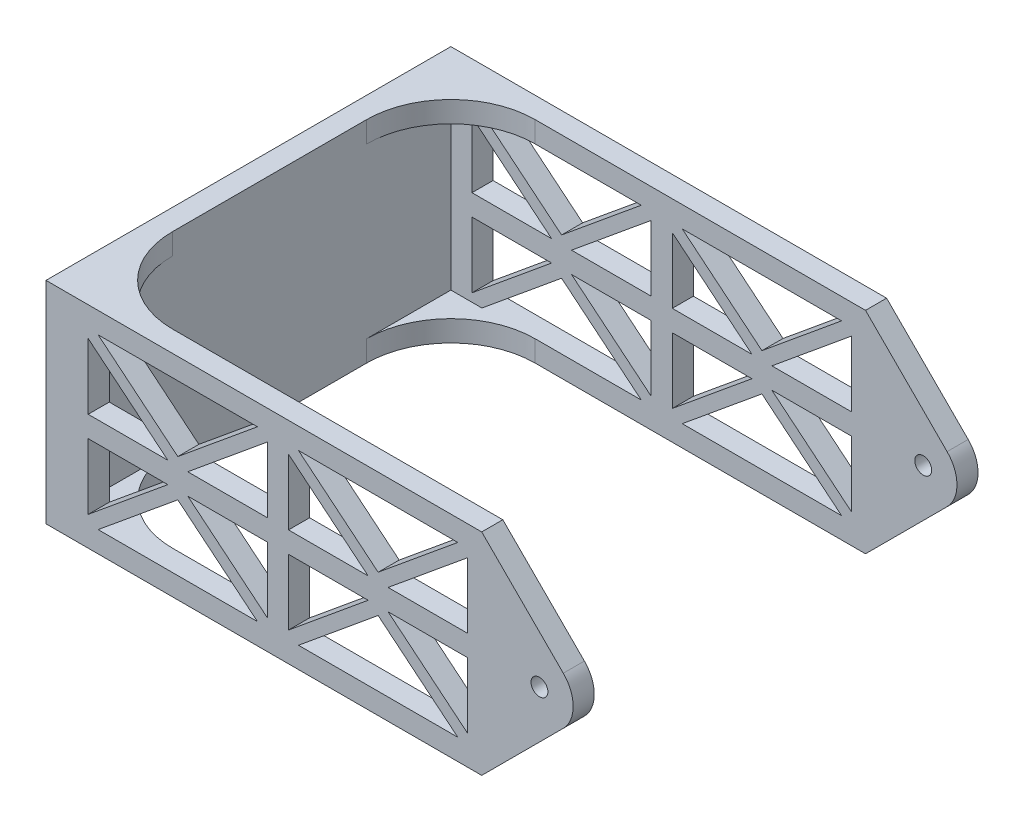
SolidWorks part; units mm, degrees
ref_plane "Front Plane" through (0, 0, 0) normal (0, 0, 1) x (1, 0, 0)
ref_plane "Top Plane" through (0, 0, 0) normal (0, 1, 0) x (1, 0, 0)
ref_plane "Right Plane" through (0, 0, 0) normal (1, 0, 0) x (0, 0, -1)
sketch "Sketch1" plane through (0, 0, 0) normal (0, 1, 0) x (1, 0, 0)
  line L0 (0, 0) -> (125, 0)
  line L1 (125, 0) -> (125, 5)
  line L2 (125, 5) -> (5, 5)
  line L3 (5, 5) -> (5, 91)
  line L5 (0, 96) -> (0, 0)
  line L6 (125, 96) -> (125, 91)
  line L7 (0, 96) -> (125, 96)
  line L8 (125, 91) -> (5, 91)
  dimension "D1" = 86
  dimension "D2" = 5
  dimension "D3" = 120
  dimension "D4" = 5
  dimension "D5" = 5
extrude "Boss-Extrude1" add sketch "Sketch1" along normal blind 50
sketch "Sketch2" plane through (0, 0, 0) normal (0, 0, 1) x (1, 0, 0)
  line L0 (0, 0) -> (125, 0) construction
  line L2 (125, 50) -> (125, 0) construction
  circle A0 centre (117, 25) radius 2
  dimension "D3" = 4
  dimension "D1" = 25
  dimension "D2" = 8
extrude "Cut-Extrude1" cut sketch "Sketch2" against normal through all
sketch "Sketch3" plane through (0, 0, 0) normal (0, 0, 1) x (1, 0, 0)
  line L0 (122.6569, 30.6569) -> (103.3137, 50)
  line L1 (0, 50) -> (125, 50) construction
  line L2 (103.3137, 50) -> (0, 50)
  line L3 (0, 50) -> (0, 0)
  line L4 (0, 0) -> (103.3137, 0)
  line L5 (0, 0) -> (125, 0) construction
  line L6 (103.3137, 0) -> (122.6569, 19.3431)
  line L7 (103.3137, 50) -> (125, 50)
  line L8 (125, 50) -> (125, 0)
  line L9 (125, 0) -> (103.3137, 0)
  line L10 (103.3137, 0) -> (125, 0)
  line L11 (10, 45) -> (100, 45)
  line L12 (100, 45) -> (100, 27.5)
  line L13 (100, 27.5) -> (10, 27.5)
  line L14 (10, 27.5) -> (10, 45)
  line L15 (0, 25) -> (117, 25) construction
  line L16 (52.5, 27.5) -> (52.5, 45)
  line L17 (52.5, 45) -> (57.5, 45)
  line L18 (57.5, 45) -> (57.5, 27.5)
  line L19 (57.5, 27.5) -> (52.5, 27.5)
  line L20 (10, 45) -> (31.25, 27.5) construction
  line L21 (31.25, 27.5) -> (52.5, 45) construction
  line L22 (31.25, 27.5) -> (31.25, 45) construction
  line L23 (10, 43.0568) -> (28.8904, 27.5)
  line L24 (28.8904, 27.5) -> (33.6096, 27.5)
  line L25 (33.6096, 27.5) -> (52.5, 43.0568)
  line L26 (55, 45) -> (55, 27.5) construction
  line L27 (50.1404, 45) -> (31.25, 29.4432)
  line L28 (31.25, 29.4432) -> (12.3596, 45)
  line L29 (76.3904, 27.5) -> (57.5, 43.0568)
  line L30 (100, 43.0568) -> (81.1096, 27.5)
  line L31 (78.75, 29.4432) -> (97.6404, 45)
  line L32 (59.8596, 45) -> (78.75, 29.4432)
  line L33 (100, 6.9432) -> (81.1096, 22.5)
  line L34 (78.75, 20.5568) -> (97.6404, 5)
  line L35 (59.8596, 5) -> (78.75, 20.5568)
  line L36 (76.3904, 22.5) -> (57.5, 6.9432)
  line L37 (100, 22.5) -> (10, 22.5)
  line L38 (100, 5) -> (100, 22.5)
  line L39 (10, 5) -> (100, 5)
  line L40 (10, 22.5) -> (10, 5)
  line L41 (52.5, 22.5) -> (52.5, 5)
  line L42 (57.5, 5) -> (57.5, 22.5)
  line L43 (50.1404, 5) -> (31.25, 20.5568)
  line L44 (33.6096, 22.5) -> (52.5, 6.9432)
  line L45 (10, 6.9432) -> (28.8904, 22.5)
  line L46 (31.25, 20.5568) -> (12.3596, 5)
  circle A0 centre (117, 25) radius 8
  line M30 (0, 0) -> (125, 0)
  line M31 (125, 0) -> (125, 50)
  line M32 (125, 50) -> (0, 50)
  dimension "D1" = 16
  dimension "D2" = 45
  dimension "D3" = 45
  dimension "D4" = 5
  dimension "D5" = 2.5
  dimension "D6" = 10
  dimension "D7" = 90
  dimension "D8" = 5
  dimension "D9" = 42.5
  dimension "D10" = 21.25
  dimension "D11" = 1.5
  dimension "D12" = 1.5
  dimension "D13" = 1.5
extrude "Cut-Extrude2" cut sketch "Sketch3" against normal blind 10 contours L25 L13 L16 | L28 L27 L11 | L23 L14 L13 | L40 L45 L37 | L43 L46 L39 | L37 L44 L41 | L42 L36 L37 | L35 L39 L34 | L33 L38 L37 | L12 L30 L13 | L11 L32 L31 | L13 L29 L18 | A0 L8 L0 M32 | A0 L6 M30 M31
ref_plane "Plane1" through (0, 0, -48) normal (0, 0, 1) x (1, 0, 0)
mirror "Mirror3" about plane through (0, 0, -48) normal (0, 0, 1) of "Cut-Extrude2"
sketch "Sketch6" plane through (0, 50, 0) normal (0, 1, 0) x (1, 0, 0)
  line L0 (5, 5) -> (25, 5)
  line L1 (103.3137, 5) -> (5, 5) construction
  line L3 (5, 5) -> (5, 91) construction
  line L4 (5, 25) -> (5, 5)
  arc A0 (5, 25) -> (25, 5) centre (25, 25) ccw
  dimension "D1" = 20
  dimension "D2" = 20
  dimension "D3" = 20
extrude "Boss-Extrude3" add sketch "Sketch6" against normal blind 5
ref_plane "Plane2" through (0, 25, 0) normal (0, 1, 0) x (1, 0, 0)
mirror "Mirror4" about plane through (0, 25, 0) normal (0, 1, 0) of "Boss-Extrude3"
mirror "Mirror5" about plane through (0, 0, -48) normal (0, 0, 1) of "Mirror4", "Boss-Extrude3"
